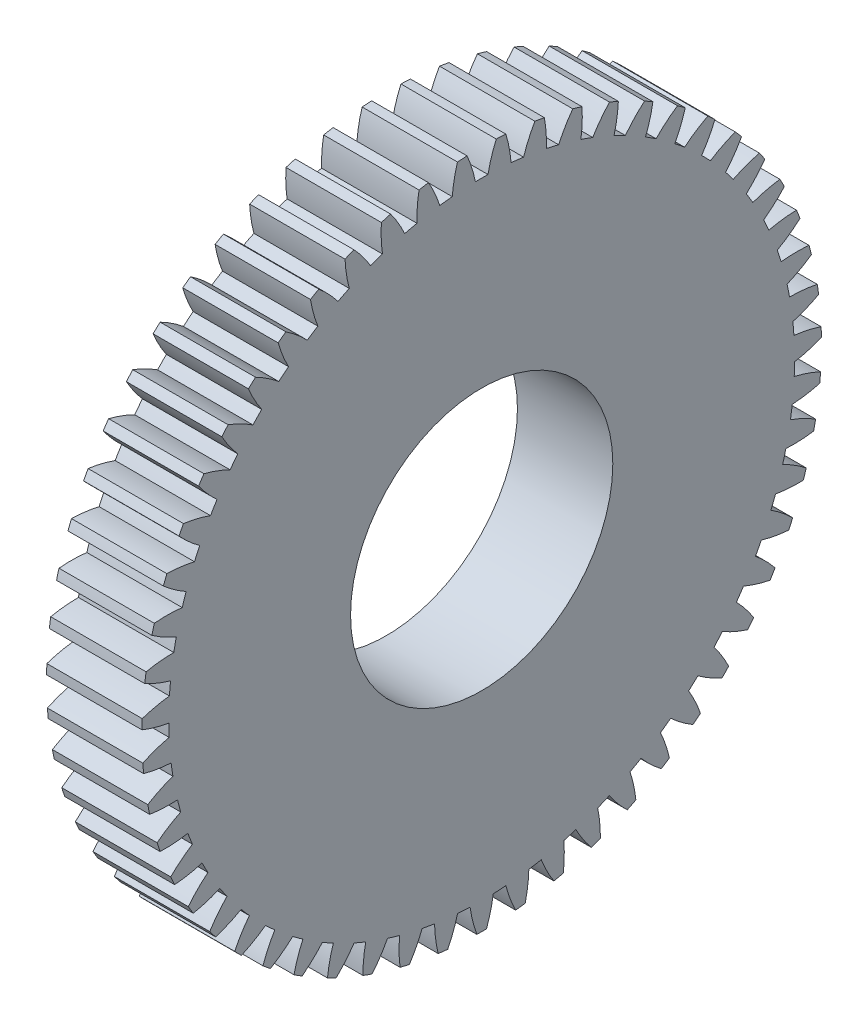
SolidWorks part; units mm, degrees
ref_plane "Plane1" through (0, 0, 0) normal (0, 0, 1) x (1, 0, 0)
ref_plane "Plane2" through (0, 0, 0) normal (0, 1, 0) x (1, 0, 0)
ref_plane "Plane3" through (0, 0, 0) normal (1, 0, 0) x (0, 0, -1)
other "Configuration Table"
sketch "HoldingSke" plane through (0, 0, 0) normal (0, 1, 0) x (1, 0, 0)
  line L0 (0, 0) -> (1.1472, -1.6383)
  line L1 (-15, 0) -> (100, 0) construction
  line L2 (0, 0) -> (-2.1039, 2.3779)
  line L3 (0, 0) -> (-11.863, 4.5341)
  line L4 (0, 0) -> (4.9534, 7.0742)
  line L5 (0, 0) -> (-46.8476, -17.4728)
  line L6 (0, 0) -> (-3.3159, -2.2372)
  line L7 (-2.1039, 2.3779) -> (8.6586, 51.2059)
  line L8 (-76.2, 54.61) -> (-74.4, 54.61)
  line L9 (-67.7845, 28.3722) -> (-49.3413, 33.142)
  line L10 (-76.2, 71.12) -> (104.1128, 71.12)
  line L11 (0, 0) -> (-4, 0)
  line L12 (-76.2, 101.6) -> (-76.181, 101.6)
  line L13 (24.9733, 27.94) -> (52.9518, 28.4284)
  line L14 (24.9733, 27.94) -> (24.9743, 27.94)
  line L15 (24.9733, 27.94) -> (100.4006, 29.5858)
  line L16 (-63.627, -0.5) -> (-12.827, -0.5)
  circle A0 centre (0, 0) radius 5.5
  circle A1 centre (0, 0) radius 13.124
  circle A2 centre (0, 0) radius 37.5
  circle A3 centre (0, 0) radius 5.5
  dimension "MHD" = 26.248
  dimension "Hub_dia" = 75
  dimension "Bore" = 11
  dimension "MBD" = 11
  dimension "Num_teeth" = 55
  dimension "Pitch" = 2
  dimension "Overall_len" = 50
  dimension "Show_teeth" = 55
  dimension "Thickness" = 4
  dimension "OAL" = 50.0001
  dimension "T_dim" = 1.8
  dimension "Ap" = 14.5
  dimension "H" = 19.05
  dimension "Pitch_radius" = 180.3128
  dimension "Width" = 4
  dimension "Backlash" = 0.019
  dimension "Addendum_fac" = 1
  dimension "Dedendum_fac" = 1.25
  dimension "Clearance_fac" = 0.25
  dimension "Dedendum_add" = 0.001
  dimension "Module" = 0.5
sketch "BasProSke" plane through (0, 0, 0) normal (0, 1, 0) x (1, 0, 0)
  line L0 (-10, 0) -> (60, 0) construction
  line L1 (0, 0) -> (0, 14.25)
  line L2 (0, 0) -> (4, 0)
  line L3 (4, 0) -> (4, 14.25)
  line L4 (4, 14.25) -> (0, 14.25)
  dimension "Thickness" = 4
  dimension "Diameter" = 28.5
revolve "Base-Revolve" add sketch "BasProSke" angle 360 about L0
sketch "TooCutSke" plane through (0, 0, 0) normal (1, 0, 0) x (0, 0, -1)
  line L1 (0, 0) -> (0, 107) construction
  line L2 (0, 0) -> (-0.4259, 13.7434) construction
  line L3 (0, 0) -> (-1.5694, 27.4458) construction
  line L4 (-0.4259, 13.7434) -> (-0.7847, 13.7229) construction
  arc A0 (0.264, 13.1213) -> (-0.264, 13.1213) centre (0, 0) ccw
  arc A1 (0.6231, 14.2618) -> (-0.6231, 14.2618) centre (0, 0) ccw
  circle A2 centre (0, 0) radius 13.75 construction
  circle A3 centre (0, 0) radius 13.312 construction
  arc A4 (-0.264, 13.1213) -> (-0.6231, 14.2618) centre (-5.6586, 12.0495) ccw
  arc A5 (0.6231, 14.2618) -> (0.264, 13.1213) centre (5.6586, 12.0495) ccw
  dimension "Root_dia" = 26.248
  dimension "Overcut_dia" = 28.5508
  dimension "Pitch_dia" = 27.5
  dimension "Base_dia" = 26.6241
  dimension "Flank_rad" = 5.5
  dimension "Half_ang" = 3.273
  dimension "Half_CT" = 0.3594
extrude "ToothCut" cut sketch "TooCutSke" along normal through all
fillet "Breaks" [suppressed] radius 0.01
fillet "RootFillets" [suppressed] radius 0.126
pattern_circular "TeethCuts" count 55 every 6.545 about axis through (-10, 0, 0) along (1, 0, 0) of "ToothCut", "RootFillets", "Breaks"
sketch "HubNeaOneSke" plane through (0, 0, 0) normal (-1, 0, 0) x (0, 0, 1)
  circle A0 centre (0, 0) radius 13.124
  dimension "Diameter" = 26.248
extrude "HubNearOne" [suppressed] add sketch "HubNeaOneSke" along normal blind 46.0001
sketch "HubNeaBotSke" plane through (0, 0, 0) normal (-1, 0, 0) x (0, 0, 1)
  circle A0 centre (0, 0) radius 13.124
  dimension "Diameter" = 26.248
extrude "HubNearBoth" [suppressed] add sketch "HubNeaBotSke" along normal blind 23
ref_plane "FarPln" through (4, 0, 0) normal (1, 0, 0) x (0, 0, -1)
sketch "HubFarSke" plane through (4, 0, 0) normal (1, 0, 0) x (0, 0, -1)
  circle A0 centre (0, 0) radius 13.124
  dimension "Diameter" = 26.248
extrude "HubFar" [suppressed] add sketch "HubFarSke" along normal blind 23
sketch "BorSke" plane through (0, 0, 0) normal (1, 0, 0) x (0, 0, -1)
  circle A0 centre (0, 0) radius 5.5
  dimension "Diameter" = 11
extrude "Bore" cut sketch "BorSke" along normal mid plane 100.0001
sketch "KeySke" plane through (0, 0, 0) normal (1, 0, 0) x (0, 0, -1)
  line L0 (-2, 0) -> (-2, 7.3)
  line L1 (-2, 7.3) -> (2, 7.3)
  line L2 (2, 7.3) -> (2, 0)
  line L3 (0, 0) -> (0, 34) construction
  line L4 (-2, 0) -> (2, 0)
  dimension "Width" = 4
  dimension "Offset" = 7.3
extrude "Keyway" [suppressed] cut sketch "KeySke" along normal mid plane 100.0001
pattern_circular "Keyway2" [suppressed] count 2 every 90 about axis through (-10, 0, 0) along (1, 0, 0)
equation "' \"Module@HoldingSke\" = 6.35"
equation "' \"Num_teeth@HoldingSke\" = 12"
equation "' \"Ap@HoldingSke\" =  20"
equation "' \"Ap@HoldingSke\" = 20"
equation "' \"Width@HoldingSke\" = 0.5 * 25.4"
equation "' \"Hub_dia@HoldingSke\"= 1 * 25.4"
equation "' \"Hub_dia@HoldingSke\" = 1 * 25.4"
equation "' \"Overall_len@HoldingSke\" = 1.0 * 25.4"
equation "' \"Bore@HoldingSke\" = 0.75 * 25.4"
equation "' \"T_dim@HoldingSke\" = 0.1 * 25.4"
equation "' \"Width@KeySke\" = 0.25 * 25.4"
equation "' \"Show_teeth@HoldingSke\" = 13"
equation "' \"Backlash@HoldingSke\" = 0.009 * 25.4"
equation "' \"Addendum_fac@HoldingSke\" = 1.0"
equation "' \"Dedendum_fac@HoldingSke\" = 1.25"
equation "' \"Dedendum_add@HoldingSke\" = 0.00005 * 25.4"
equation "' \"Clearance_fac@HoldingSke\" = 0.25"
equation "\"Pitch@HoldingSke\" = 1 / \"Module@HoldingSke\""
equation "\"Overcut_dia@TooCutSke\" = (\"Num_teeth@HoldingSke\" + 2 * \"Addendum_fac@HoldingSke\") / \"Pitch@HoldingSke\" + 0.002 * 25.4"
equation "\"Pitch_dia@TooCutSke\" = \"Num_teeth@HoldingSke\" / \"Pitch@HoldingSke\""
equation "\"Base_dia@TooCutSke\" = \"Num_teeth@HoldingSke\" / \"Pitch@HoldingSke\" * cos((\"Ap@HoldingSke\"  * 3.14159265 / 180))"
equation "\"Root_dia@TooCutSke\" = (\"Num_teeth@HoldingSke\" + 2) / \"Pitch@HoldingSke\" - 2 * (\"Addendum_fac@HoldingSke\" + \"Dedendum_fac@HoldingSke\") / \"Pitch@HoldingSke\" - \"Dedendum_add@HoldingSke\" * 2"
equation "\"Half_ang@TooCutSke\" = 180 / \"Num_teeth@HoldingSke\""
equation "\"Half_CT@TooCutSke\" = \"Num_teeth@HoldingSke\" / \"Pitch@HoldingSke\" * sin((3.14159265 / 2 / \"Num_teeth@HoldingSke\")) / 2 - 7 * \"Backlash@HoldingSke\" / 4"
equation "\"Flank_rad@TooCutSke\" = \"Num_teeth@HoldingSke\" / \"Pitch@HoldingSke\" / 5"
equation "\"Radius@RootFillets\" = \"Clearance_fac@HoldingSke\" / \"Pitch@HoldingSke\" + \"Dedendum_add@HoldingSke\""
equation "\"Break_rad@Breaks\" = 0.02 / \"Pitch@HoldingSke\""
equation "\"Thickness@HoldingSke\" = \"Width@HoldingSke\""
equation "\"OAL@HoldingSke\" = \"Thickness@HoldingSke\""
equation "\"MHD@HoldingSke\" = (\"Num_teeth@HoldingSke\" + 2) / \"Pitch@HoldingSke\" - 2 * (\"Addendum_fac@HoldingSke\" + \"Dedendum_fac@HoldingSke\")  / \"Pitch@HoldingSke\" - \"Dedendum_add@HoldingSke\" * 2"
equation "\"MBD@HoldingSke\" = (\"Num_teeth@HoldingSke\" + 2) / \"Pitch@HoldingSke\" - 2 * (\"Addendum_fac@HoldingSke\" + \"Dedendum_fac@HoldingSke\")  / \"Pitch@HoldingSke\" - \"Dedendum_add@HoldingSke\" * 2 - 0.002 * 25.4"
equation "\"MHD@HoldingSke\" = ((sgn( \"MHD@HoldingSke\" - \"Hub_dia@HoldingSke\" )-1)*( \"MHD@HoldingSke\" - \"Hub_dia@HoldingSke\" ))/-2+ \"Hub_dia@HoldingSke\""
equation "\"MBD@HoldingSke\" = ((sgn( \"MBD@HoldingSke\" - \"Bore@HoldingSke\" )-1)*( \"MBD@HoldingSke\" - \"Bore@HoldingSke\" ))/-2+ \"Bore@HoldingSke\""
equation "\"OAL@HoldingSke\" = ((sgn( \"OAL@HoldingSke\" - \"Overall_len@HoldingSke\" )+1)*( \"OAL@HoldingSke\" - \"Overall_len@HoldingSke\" ))/2 + \"Overall_len@HoldingSke\" + 0.000002 * 25.4"
equation "\"Num_teeth@TeethCuts\" = int( \"Show_teeth@HoldingSke\" ) + 1"
equation "\"Num_teeth@TeethCuts\" = ((sgn( \"Num_teeth@TeethCuts\" - \"Num_teeth@HoldingSke\" )-1)*( \"Num_teeth@TeethCuts\" - \"Num_teeth@HoldingSke\" ))/-2+ \"Num_teeth@HoldingSke\""
equation "\"Num_teeth@TeethCuts\" = ((sgn( \"Num_teeth@TeethCuts\" - 2.0)+1)*( \"Num_teeth@TeethCuts\" - 2.0))/2 +2.0"
equation "\"Angle@TeethCuts\" = 360.0 / \"Num_teeth@HoldingSke\""
equation "\"Diameter@BasProSke\" = (\"Num_teeth@HoldingSke\" + 2 * \"Addendum_fac@HoldingSke\") / \"Pitch@HoldingSke\""
equation "\"Thickness@BasProSke\"  = \"Thickness@HoldingSke\""
equation "' \"Fillet_rad@BasProSke\" =  \"Thickness@HoldingSke\" * 0.05"
equation "' \"Fillet_rad@BasProSke\" = \"Thickness@HoldingSke\" * 0.05"
equation "\"MHD@HoldingSke\" = ((sgn( \"MHD@HoldingSke\" - \"Root_dia@TooCutSke\" )-1)*( \"MHD@HoldingSke\" - \"Root_dia@TooCutSke\" ))/-2+ \"Root_dia@TooCutSke\""
equation "\"Diameter@HubNeaOneSke\" = \"MHD@HoldingSke\""
equation "\"Length@HubNearOne\" = \"OAL@HoldingSke\" - \"Thickness@BasProSke\""
equation "\"Diameter@HubNeaBotSke\" = \"MHD@HoldingSke\""
equation "\"Length@HubNearBoth\" = ( \"OAL@HoldingSke\" - \"Thickness@BasProSke\" ) / 2.0"
equation "\"Thickness@FarPln\" = \"Thickness@BasProSke\""
equation "\"Diameter@HubFarSke\" = \"MHD@HoldingSke\""
equation "\"Length@HubFar\" = ( \"OAL@HoldingSke\" - \"Thickness@BasProSke\" ) / 2.0"
equation "\"Diameter@BorSke\" = \"MBD@HoldingSke\""
equation "\"D1@Bore\" = \"OAL@HoldingSke\" * 2.0"
equation "\"D1@Keyway\" = \"OAL@HoldingSke\" * 2.0"
equation "\"Offset@KeySke\" = \"T_dim@HoldingSke\" + \"MBD@HoldingSke\" / 2.0"
